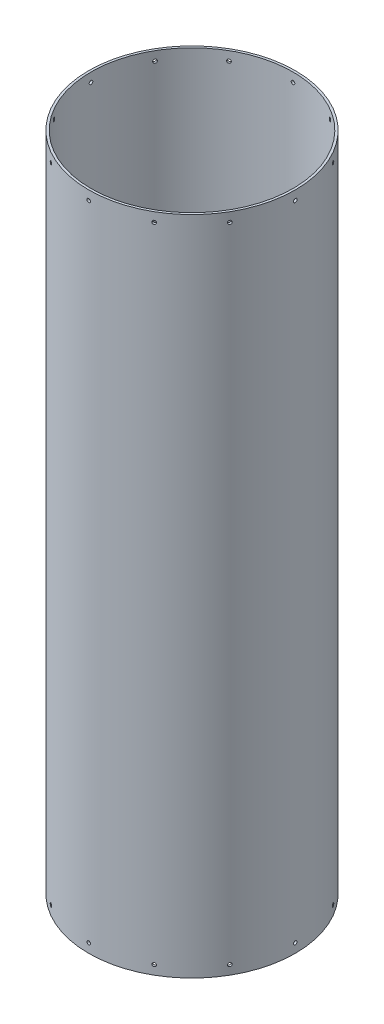
SolidWorks part; units mm, degrees
material "Hexcel AS4C (3000 Filaments)"
ref_plane "Front Plane" through (0, 0, 0) normal (0, 0, 1) x (1, 0, 0)
ref_plane "Top Plane" through (0, 0, 0) normal (0, 1, 0) x (1, 0, 0)
ref_plane "Right Plane" through (0, 0, 0) normal (1, 0, 0) x (0, 0, -1)
sketch "Sketch1" plane through (0, 0, 0) normal (0, 1, 0) x (1, 0, 0)
  circle A0 centre (0, 0) radius 139.7
  circle A1 centre (0, 0) radius 142.875
  dimension "D1" = 279.4
  dimension "D2" = 3.175
extrude "Boss-Extrude1" add sketch "Sketch1" along normal blind 914.4
ref_plane "Plane1" through (142.875, 0, 0) normal (1, 0, 0) x (0, 0, -1)
hole_wizard "#10 (0.1935) Diameter Hole1" positions "Sketch2" profile "Sketch3" hole size "#10" standard "ANSI Inch"
sketch "Sketch2" plane through (142.875, 0, 0) normal (1, 0, 0) x (0, 0, -1)
  line L0 (0, 157.1625) -> (0, -157.1625) construction
  line L1 (142.875, 914.4) -> (-142.875, 914.4) construction
  point P0 (0, 901.7)
  dimension "D1" = 12.7
sketch "Sketch3" plane through (142.875, 901.7, 0) normal (0, 1, 0) x (0, 0, -1)
  line L0 (0, 0) -> (0, 333.7101)
  line L1 (0, 333.7101) -> (2.4574, 333.7101)
  line L2 (2.4574, 333.7101) -> (2.4574, 0)
  line L5 (2.4574, 0) -> (0, 0)
  line L11 (0, -6.35) -> (0, 107.95) construction
  dimension "Thru Hole Dia." = 4.9149
  dimension "Thru Hole Depth" = 333.7101
pattern_circular "CirPattern1" count 12 over 360 about axis through (0, 914.4, 0) along (0, 1, 0) of "#10 (0.1935) Diameter Hole1"
ref_plane "Plane2" through (0, 457.2, 0) normal (0, 1, 0) x (1, 0, 0)
mirror "Mirror1" about plane through (0, 457.2, 0) normal (0, 1, 0) of "CirPattern1", "#10 (0.1935) Diameter Hole1"
